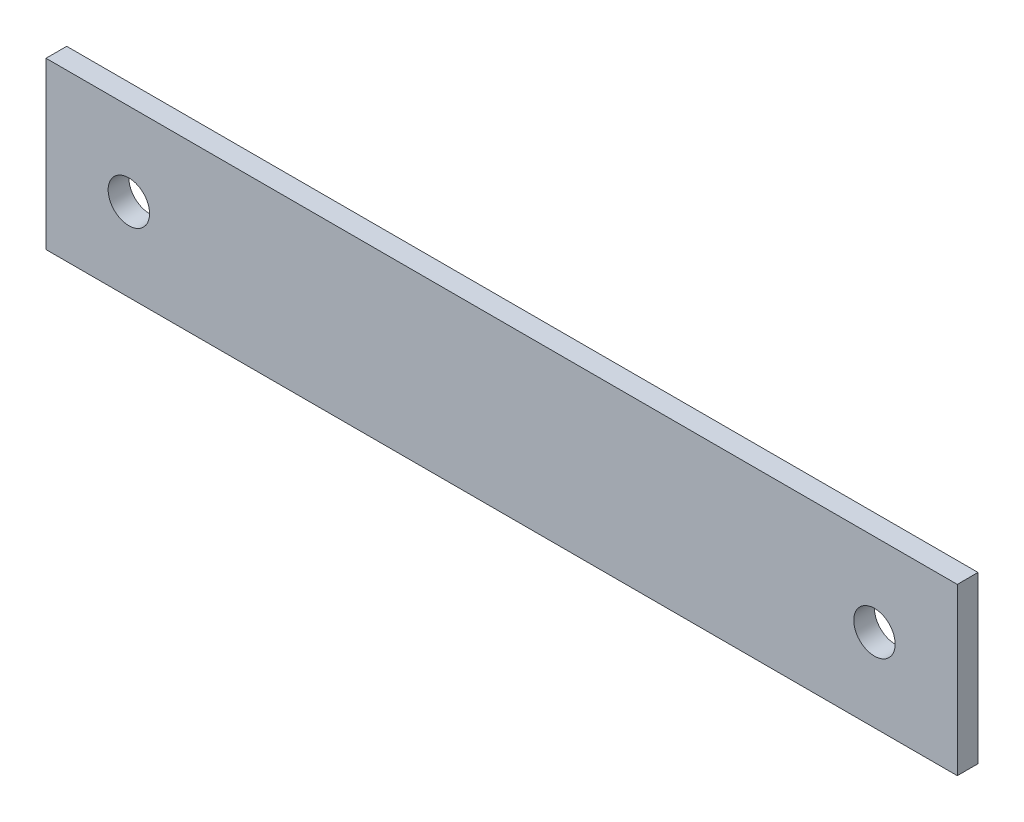
SolidWorks part; units mm, degrees
ref_plane "Front Plane" through (0, 0, 0) normal (0, 0, 1) x (1, 0, 0)
ref_plane "Top Plane" through (0, 0, 0) normal (0, 1, 0) x (1, 0, 0)
ref_plane "Right Plane" through (0, 0, 0) normal (1, 0, 0) x (0, 0, -1)
sketch "Sketch1" plane through (0, 0, 0) normal (0, 0, 1) x (1, 0, 0)
  line L1 (0, 0) -> (139.7, 0)
  line L2 (0, 0) -> (0, 25.4)
  line L3 (0, 25.4) -> (139.7, 25.4)
  line L4 (139.7, 0) -> (139.7, 25.4)
  circle A0 centre (12.7, 12.7) radius 3.175
  circle A1 centre (127, 12.7) radius 3.175
  dimension "D3" = 6.35
  dimension "D1" = 139.7
  dimension "D2" = 25.4
  dimension "D4" = 12.7
  dimension "D5" = 12.7
  dimension "D6" = 12.7
  dimension "D7" = 12.7
extrude "Boss-Extrude1" add sketch "Sketch1" along normal blind 3.175
